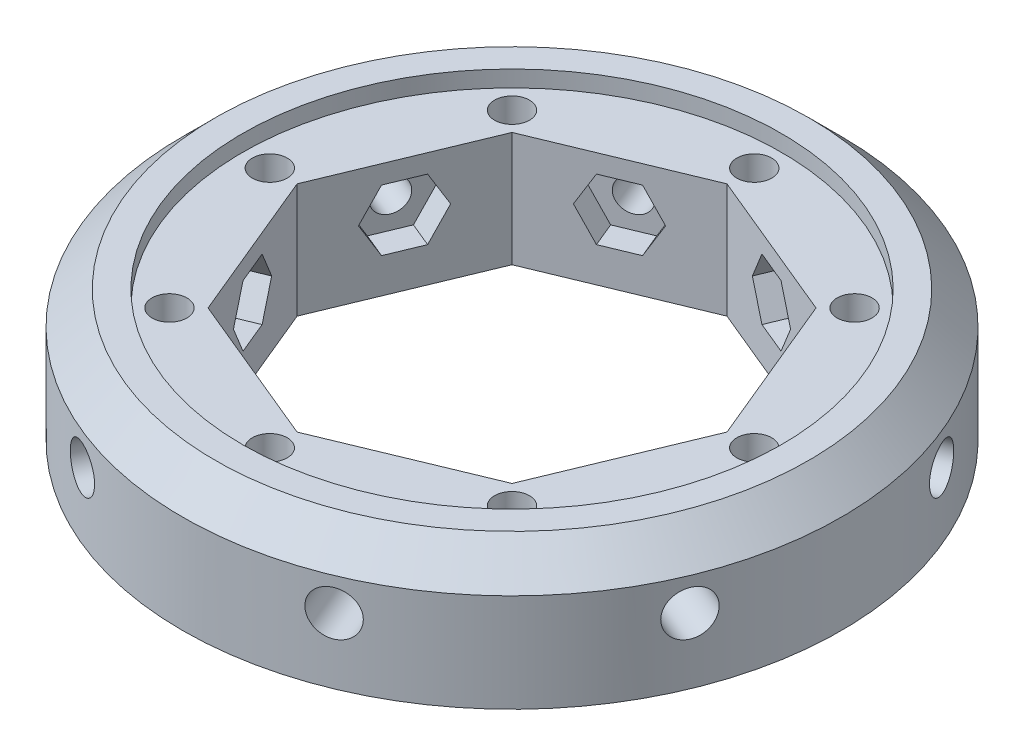
SolidWorks part; units mm, degrees
ref_plane "前视基准面" through (0, 0, 0) normal (0, 0, 1) x (1, 0, 0)
ref_plane "上视基准面" through (0, 0, 0) normal (0, 1, 0) x (1, 0, 0)
ref_plane "右视基准面" through (0, 0, 0) normal (1, 0, 0) x (0, 0, -1)
other "Configuration Table"
sketch "草图1" plane through (0, 0, 0) normal (0, 1, 0) x (1, 0, 0)
  line L5 (0, 39.1969) -> (0, 0) construction
  line L6 (-11.5558, 27.8983) -> (0, 0) construction
  line L7 (-27.7164, 27.7164) -> (0, 39.1969) construction
  line L8 (-11.5558, 27.8983) -> (-13.8582, 33.4566) construction
  line L9 (-22.2263, 37.9802) -> (-16.8687, 25.0459)
  line L10 (-11.1397, 42.5724) -> (-5.7822, 29.6381)
  line L11 (-22.2263, 37.9802) -> (-11.1397, 42.5724)
  line L21 (0, 19.6962) -> (-13.9273, 13.9273)
  line L22 (-13.9273, 13.9273) -> (-19.6962, 0)
  line L23 (-19.6962, 0) -> (-13.9273, -13.9273)
  line L24 (-13.9273, -13.9273) -> (0, -19.6962)
  line L25 (0, -19.6962) -> (13.9273, -13.9273)
  line L26 (13.9273, -13.9273) -> (19.6962, 0)
  line L27 (19.6962, 0) -> (13.9273, 13.9273)
  line L28 (13.9273, 13.9273) -> (0, 19.6962)
  circle A1 centre (0, 0) radius 30.1969
  circle A2 centre (0, 39.1969) radius 9
  circle A3 centre (27.7164, 27.7164) radius 9
  circle A4 centre (39.1969, 0) radius 9
  circle A5 centre (27.7164, -27.7164) radius 9
  circle A6 centre (0, -39.1969) radius 9
  circle A7 centre (-27.7164, -27.7164) radius 9
  circle A8 centre (-39.1969, 0) radius 9
  circle A9 centre (-27.7164, 27.7164) radius 9
  circle A10 centre (0, 0) radius 18.1969 construction
  point P21 (0, 0)
  dimension "D2" = 18
  dimension "D3" = 12
  dimension "D4" = 14
  dimension "D5" = 12
  dimension "D1" = 8
extrude "凸台-拉伸1" add sketch "草图1" along normal blind 12 contours A1 L28 L27 L26 L25 L24 L23 L22 L21
sketch "草图2" plane through (6.9636, 0, -16.8117) normal (-0.3827, 0, 0.9239) x (0.9239, 0, 0.3827)
  line L0 (0, 0) -> (0, 12) construction
  line L1 (7.5374, 12) -> (-7.5374, 12) construction
  line L2 (7.5374, 0) -> (-7.5374, 0) construction
  line L3 (3.2332, 6) -> (1.6166, 8.8)
  line L4 (1.6166, 8.8) -> (-1.6166, 8.8)
  line L5 (-1.6166, 8.8) -> (-3.2332, 6)
  line L6 (-3.2332, 6) -> (-1.6166, 3.2)
  line L7 (-1.6166, 3.2) -> (1.6166, 3.2)
  line L8 (1.6166, 3.2) -> (3.2332, 6)
  circle A1 centre (0, 6) radius 2.8 construction
  dimension "D1" = 5.6
  dimension "D2" = 6
extrude "切除-拉伸1" cut sketch "草图2" against normal blind 2.4
sketch "草图3" plane through (7.8821, 0, -19.029) normal (-0.3827, 0, 0.9239) x (0.9239, 0, 0.3827)
  line L0 (0, 3.2) -> (0, 8.8) construction
  line L1 (-1.6166, 3.2) -> (1.6166, 3.2) construction
  line L2 (1.6166, 8.8) -> (-1.6166, 8.8) construction
  circle A2 centre (0, 6) radius 1.5
  dimension "D1" = 3
extrude "切除-拉伸2" cut sketch "草图3" against normal blind 3.6
sketch "草图6" plane through (9.2597, 0, -22.355) normal (-0.3827, 0, 0.9239) x (0.9239, 0, 0.3827)
  circle A0 centre (0, 6) radius 2.05
  circle A1 centre (0, 6) radius 1.5 construction
  dimension "D1" = 4.1
extrude "切除-拉伸3" cut sketch "草图6" against normal through all
pattern_circular "阵列(圆周)25" count 8 every 45 about axis through (0, 0, 0) along (0, 1, 0) of "切除-拉伸3", "切除-拉伸2", "切除-拉伸1"
chamfer "倒角1" distance 3 angle 45 1 edges at (0, 12, 30.1969)
sketch "草图7" plane through (0, 12, 0) normal (0, 1, 0) x (1, 0, 0)
  line L0 (0, 0) -> (0, 19.6962) construction
  line L1 (0, 19.6962) -> (0, 24.6962) construction
  circle A0 centre (0, 0) radius 24.6962
  dimension "D1" = 5
extrude "切除-拉伸4" cut sketch "草图7" against normal blind 1.5
sketch "草图8" plane through (0, 10.5, 0) normal (0, 1, 0) x (1, 0, 0)
  line L0 (0, 24.6962) -> (0, 19.6962) construction
  circle A0 centre (0, 0) radius 24.6962 construction
  circle A1 centre (0, 22.1962) radius 1.6
  circle A2 centre (15.6951, 15.6951) radius 1.6
  circle A3 centre (22.1962, 0) radius 1.6
  circle A4 centre (15.6951, -15.6951) radius 1.6
  circle A5 centre (0, -22.1962) radius 1.6
  circle A6 centre (-15.6951, -15.6951) radius 1.6
  circle A7 centre (-22.1962, 0) radius 1.6
  circle A8 centre (-15.6951, 15.6951) radius 1.6
  point P23 (0, 0)
  dimension "D1" = 3.2
  dimension "D2" = 8
extrude "切除-拉伸5" cut sketch "草图8" against normal through all
